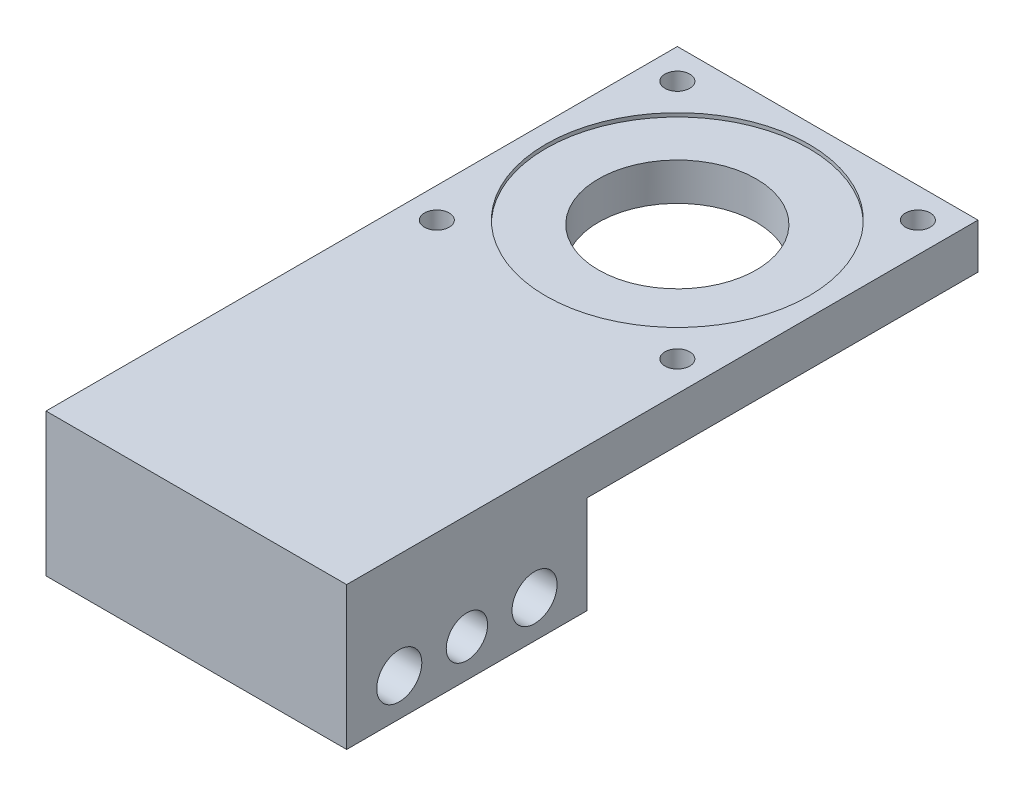
SolidWorks part; units mm, degrees
ref_plane "Front Plane" through (0, 0, 0) normal (0, 0, 1) x (1, 0, 0)
ref_plane "Top Plane" through (0, 0, 0) normal (0, 1, 0) x (1, 0, 0)
ref_plane "Right Plane" through (0, 0, 0) normal (1, 0, 0) x (0, 0, -1)
sketch "Sketch1" plane through (0, 0, 0) normal (0, 1, 0) x (1, 0, 0)
  line L0 (-20, 20) -> (-20, -64)
  line L1 (-16, -16) -> (16, -16) construction
  line L2 (-16, -16) -> (-16, 16) construction
  line L3 (-16, 16) -> (16, 16) construction
  line L4 (16, -16) -> (16, 16) construction
  line L5 (-16, -16) -> (16, 16) construction
  line L6 (-16, 16) -> (16, -16) construction
  line L7 (-20, -64) -> (20, -64)
  line L8 (20, -64) -> (20, 20)
  line L9 (20, 20) -> (-20, 20)
  line L10 (-20, -32) -> (20, -32) construction
  line L11 (-20, -60) -> (20, -60) construction
  line L12 (20, -54) -> (-20, -54) construction
  line L13 (-20, -50.5) -> (20, -50.5) construction
  line L14 (20, -45.5) -> (-20, -45.5) construction
  line L15 (-20, -36) -> (20, -36) construction
  line L16 (20, -42) -> (-20, -42) construction
  line L17 (0, -36) -> (0, -42) construction
  line L18 (0, -42) -> (0, -45.5) construction
  line L19 (0, -45.5) -> (0, -50.5) construction
  line L20 (0, -50.5) -> (0, -54) construction
  line L21 (0, -54) -> (0, -60) construction
  line L22 (0, -60) -> (0, -64) construction
  line L23 (0, -36) -> (0, -32) construction
  circle A0 centre (0, 0) radius 10.5
  circle A1 centre (-16, 16) radius 4 construction
  circle A3 centre (-16, 16) radius 2 construction
  circle A4 centre (0, 0) radius 17.5 construction
  point P0 (0, 0)
  point P37 (0, -39)
  point P38 (0, -57)
  point P39 (0, 20)
  dimension "D2" = 4
  dimension "D3" = 8
  dimension "D6" = 21
  dimension "D12" = 35
  dimension "D1" = 32
  dimension "D5" = 40
  dimension "D7" = 32
  dimension "D8" = 5
  dimension "D9" = 6
  dimension "D10" = 18
  dimension "D11" = 4
extrude "Boss-Extrude1" add sketch "Sketch1" along normal blind 6
sketch "Sketch2" plane through (0, 0, 0) normal (0, -1, 0) x (1, 0, 0)
  line L1 (-20, 64) -> (20, 64)
  line L2 (-20, 64) -> (-20, 32)
  line L3 (-20, 32) -> (20, 32)
  line L4 (20, 64) -> (20, 32)
extrude "Boss-Extrude2" add sketch "Sketch2" along normal blind 13
sketch "Sketch3" plane through (20, 0, 0) normal (1, 0, 0) x (0, 0, -1)
  line L0 (-57, -3) -> (-57, -13)
  line L2 (-32, -13) -> (-64, -13) construction
  line L3 (-48, -3) -> (-48, -13)
  line L4 (-39, -3) -> (-39, -13)
  line L5 (-64, 0) -> (20, 0) construction
  line L8 (-45.5, 0) -> (-50.5, 0) construction
  point P3 (-48, 0)
  dimension "D1" = 10
hole_wizard "Ø6.0mm Dowel Hole1" positions "Sketch4" profile "Sketch5" hole size "Ø6.0" standard "ANSI Metric" end condition through all
sketch "Sketch4" plane through (20, 0, 0) normal (1, 0, 0) x (0, 0, -1)
  line L0 (-57, -3) -> (-57, -13) construction
  line L1 (-39, -3) -> (-39, -13) construction
  point P0 (-57, -8)
  point P4 (-39, -8)
sketch "Sketch5" plane through (20, -8, 57) normal (0, 1, 0) x (0, 0, -1)
  line L0 (0, 0) -> (0, 40)
  line L1 (0, 40) -> (3, 40)
  line L2 (3, 40) -> (3, 0)
  line L5 (3, 0) -> (0, 0)
  line L11 (0, -6.35) -> (0, 107.95) construction
  dimension "Thru Hole Dia." = 6
  dimension "Thru Hole Depth" = 40
hole_wizard "M5 Clearance Hole1" positions "Sketch8" profile "Sketch9" hole size "M5" standard "ANSI Metric" end condition through all
sketch "Sketch8" plane through (-20, 0, 0) normal (-1, 0, 0) x (0, 0, 1)
  line L0 (48, -3) -> (48, -13) construction
  point P0 (48, -8)
sketch "Sketch9" plane through (-20, -8, 48) normal (0, 1, 0) x (0, 0, 1)
  line L0 (0, 0) -> (0, 40)
  line L1 (0, 40) -> (2.75, 40)
  line L2 (2.75, 40) -> (2.75, 0)
  line L5 (2.75, 0) -> (0, 0)
  line L11 (0, -6.35) -> (0, 107.95) construction
  dimension "Thru Hole Dia." = 5.5
  dimension "Thru Hole Depth" = 40
hole_wizard "M4x0.7 Tapped Hole1" positions "Sketch10" profile "Sketch11" tap size "M4x0.7" standard "ANSI Metric" end condition through all
sketch "Sketch10" plane through (0, 0, 0) normal (0, -1, 0) x (-1, 0, 0)
  point P0 (16, 16)
  point P3 (-16, 16)
  point P6 (-16, -16)
  point P9 (16, -16)
sketch "Sketch11" plane through (-16, 0, -16) normal (1, 0, 0) x (0, 0, -1)
  line L0 (0, 0) -> (0, 6)
  line L1 (0, 6) -> (1.65, 6)
  line L2 (1.65, 6) -> (1.65, 0)
  line L5 (1.65, 0) -> (0, 0)
  line L11 (0, -6.35) -> (0, 107.95) construction
  dimension "Thru Tap Drill Dia." = 3.3
  dimension "Thru Tap Drill Depth" = 6
sketch "Sketch12" plane through (0, 6, 0) normal (0, 1, 0) x (1, 0, 0)
  circle A0 centre (0, 0) radius 17.5
  dimension "D1" = 35
extrude "Cut-Extrude1" cut sketch "Sketch12" against normal blind 0.5
sketch "Sketch13" plane through (0, 0, 0) normal (0, -1, 0) x (1, 0, 0)
  circle A0 centre (0, 0) radius 17.5 construction
  circle A1 centre (0, 0) radius 17.5
extrude "Cut-Extrude2" cut sketch "Sketch13" against normal blind 0.5
